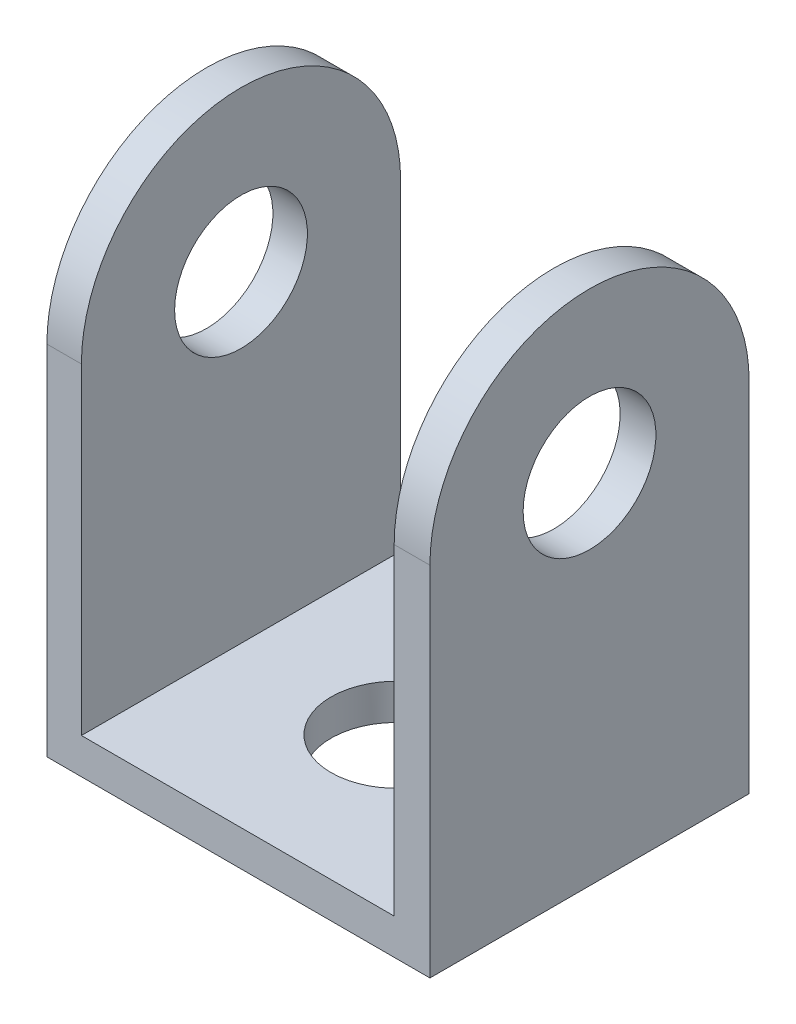
SolidWorks part; units mm, degrees
ref_plane "Front Plane" through (0, 0, 0) normal (0, 0, 1) x (1, 0, 0)
ref_plane "Top Plane" through (0, 0, 0) normal (0, 1, 0) x (1, 0, 0)
ref_plane "Right Plane" through (0, 0, 0) normal (1, 0, 0) x (0, 0, -1)
sketch "Sketch2" plane through (0, 0, 0) normal (1, 0, 0) x (0, 0, -1)
  line L0 (-7.9375, 0) -> (-7.9375, -17.78)
  line L1 (-7.9375, -17.78) -> (7.9375, -17.78)
  line L2 (7.9375, -17.78) -> (7.9375, 0)
  circle A0 centre (0, 0) radius 3.302
  circle A1 centre (0, 0) radius 7.9375
  dimension "D1" = 6.604
  dimension "D2" = 15.875
  dimension "D3" = 17.78
extrude "Boss-Extrude1" add sketch "Sketch2" along normal blind 19.05 contours A1 L0 L1 L2 | A1 A0
sketch "Sketch3" plane through (0, 0, 0) normal (0, 0, 1) x (1, 0, 0)
  line L0 (19.05, 0) -> (19.05, -17.78) construction
  line L1 (1.717, -16.002) -> (17.272, -16.002)
  line L2 (1.717, -16.002) -> (1.717, 9.398)
  line L3 (1.717, 9.398) -> (17.272, 9.398)
  line L4 (17.272, -16.002) -> (17.272, 9.398)
  line L5 (1.717, -16.002) -> (17.272, 9.398) construction
  line L6 (1.717, 9.398) -> (17.272, -16.002) construction
  line L7 (0, 0) -> (0, -17.78) construction
  line L8 (19.05, -17.78) -> (0, -17.78) construction
  point P0 (9.4945, -3.302)
  dimension "D1" = 1.778
  dimension "D2" = 1.717
  dimension "D3" = 1.778
  dimension "D4" = 25.4
extrude "Cut-Extrude1" cut sketch "Sketch3" against normal mid plane 25.4
sketch "Sketch4" plane through (0, 0, 0) normal (0, 1, 0) x (1, 0, 0)
  line L0 (1.717, 7.9375) -> (17.272, 7.9375) construction
  circle A0 centre (9.525, -0.0635) radius 3.2639
  dimension "D3" = 6.5278
  dimension "D1" = 9.525
  dimension "D2" = 8.001
extrude "Cut-Extrude2" cut sketch "Sketch4" against normal through all
sketch3d "3DSketch1"
  line L0 (0, 0, 0) -> (19.05, 0, 0) construction
  line L1 (19.05, 0, 0) -> (17.272, 0, 0) construction
  line L2 (9.525, 0, 0) -> (9.525, 0, 7.1009) construction
  line L3 (9.525, 0, 0) -> (9.525, -7.9855, 0) construction
  line L4 (0.7251, 0, 0) -> (-8.7999, 0, 0) construction
